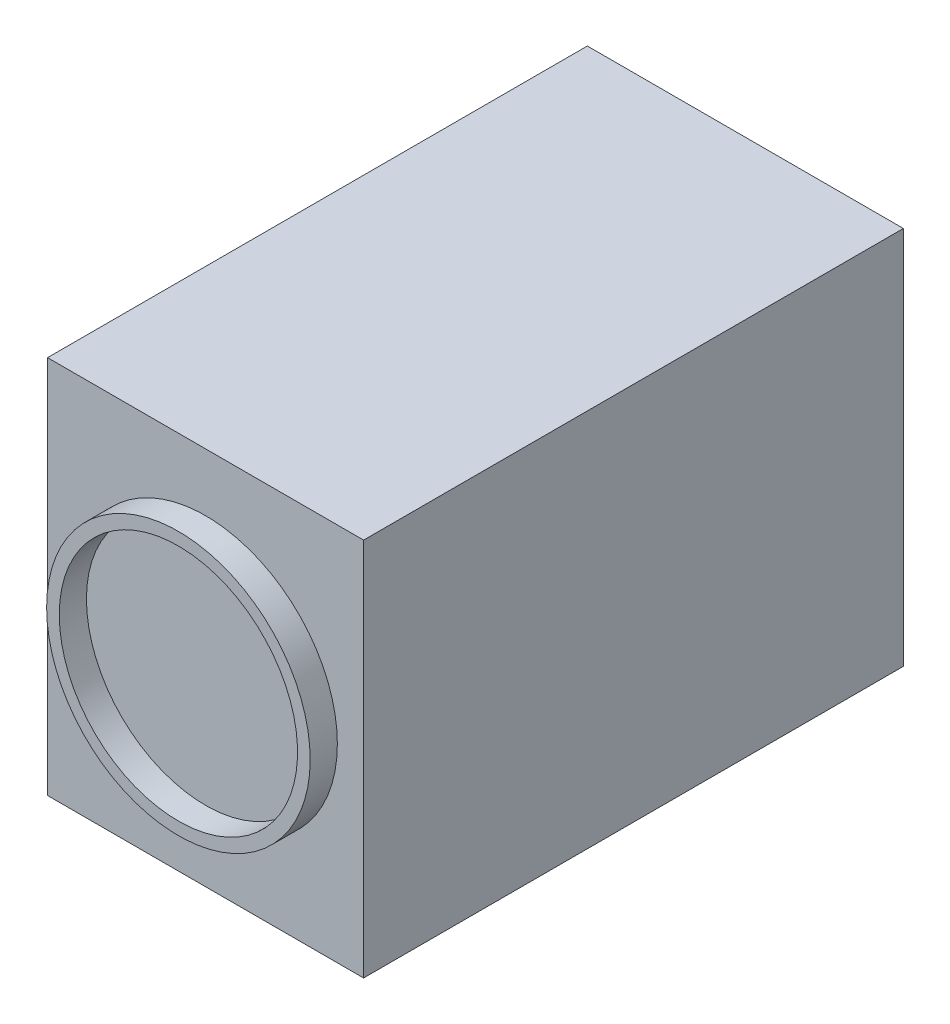
SolidWorks part; units mm, degrees
ref_plane "Front Plane" through (0, 0, 0) normal (0, 0, 1) x (1, 0, 0)
ref_plane "Top Plane" through (0, 0, 0) normal (0, 1, 0) x (1, 0, 0)
ref_plane "Right Plane" through (0, 0, 0) normal (1, 0, 0) x (0, 0, -1)
sketch "Sketch1" plane through (0, 0, 0) normal (0, 0, 1) x (1, 0, 0)
  line L1 (-25, -30) -> (25, -30)
  line L2 (-25, -30) -> (-25, 30)
  line L3 (-25, 30) -> (25, 30)
  line L4 (25, -30) -> (25, 30)
  line L5 (-25, -30) -> (25, 30) construction
  line L6 (-25, 30) -> (25, -30) construction
  point P0 (0, 0)
  dimension "D1" = 50
  dimension "D2" = 60
extrude "Boss-Extrude1" add sketch "Sketch1" along normal blind 85.4
sketch "Sketch2" plane through (0, 0, 85.4) normal (0, 0, 1) x (1, 0, 0)
  circle A0 centre (0, 0) radius 20.85
  circle A1 centre (0, 0) radius 18.85
  dimension "D1" = 41.7
  dimension "D2" = 2
extrude "Boss-Extrude2" add sketch "Sketch2" along normal blind 4.3
hole_wizard "1/4-20 Tapped Hole1" positions "Sketch4" profile "Sketch3" tap size "1/4-20" standard "ANSI Inch"
sketch "Sketch4" plane through (0, -30, 0) normal (0, -1, 0) x (-1, 0, 0)
  line L0 (0, -85.4) -> (0, -67.85) construction
  line L1 (25, -85.4) -> (-25, -85.4) construction
  point P2 (0, -67.85)
  dimension "D1" = 17.55
sketch "Sketch3" plane through (0, -30, 67.85) normal (1, 0, 0) x (0, 0, -1)
  line L0 (0, 0) -> (0, 11.6938)
  line L1 (0, 11.6938) -> (2.5527, 10.16)
  line L2 (2.5527, 10.16) -> (2.5527, 0)
  line L5 (2.5527, 0) -> (0, 0)
  line L10 (0, 11.6938) -> (-2.5527, 10.16) construction
  line L11 (0, -6.35) -> (0, 107.95) construction
  dimension "Tap Drill Dia." = 5.1054
  dimension "Tap Drill Depth" = 10.16
  dimension "Drill Angle" = 118
